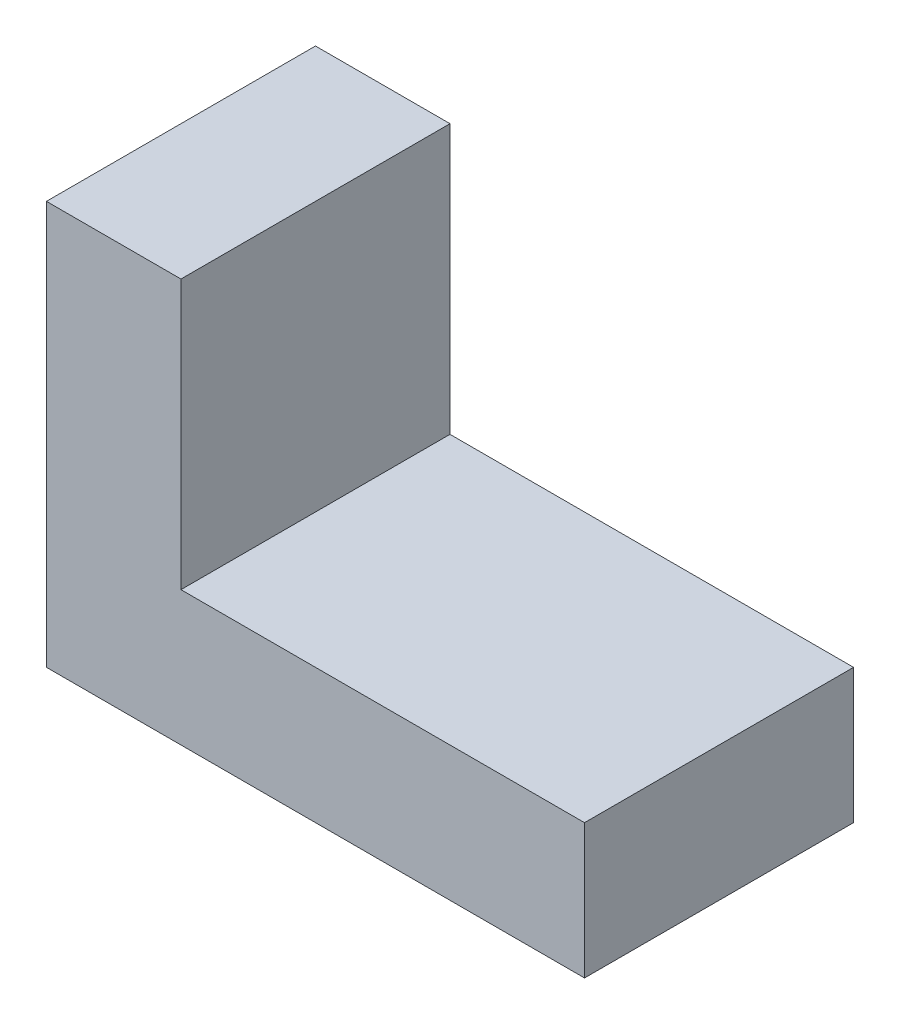
SolidWorks part; units mm, degrees
ref_plane "Front Plane" through (0, 0, 0) normal (0, 0, 1) x (1, 0, 0)
ref_plane "Top Plane" through (0, 0, 0) normal (0, 1, 0) x (1, 0, 0)
ref_plane "Right Plane" through (0, 0, 0) normal (1, 0, 0) x (0, 0, -1)
ref_plane "Plane1" through (0, 0, 20) normal (0, 0, 1) x (1, 0, 0)
sketch "Sketch1" plane through (0, 0, 20) normal (0, 0, 1) x (1, 0, 0)
  line L0 (5, 5) -> (25, 5)
  line L1 (25, 5) -> (25, 10)
  line L2 (25, 10) -> (10, 10)
  line L3 (10, 10) -> (10, 20)
  line L4 (10, 20) -> (5, 20)
  line L5 (5, 20) -> (5, 5)
extrude "Boss-Extrude1" add sketch "Sketch1" along normal blind 10
